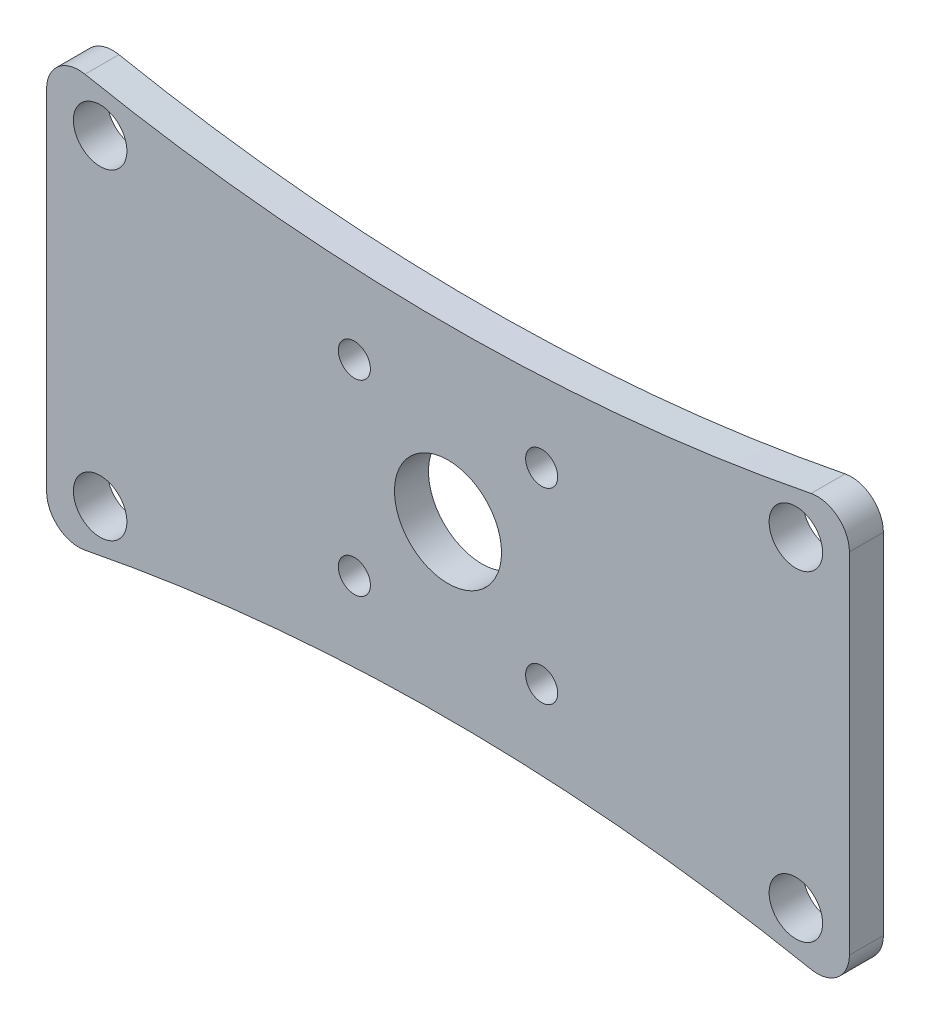
SolidWorks part; units mm, degrees
ref_plane "Front Plane" through (0, 0, 0) normal (0, 0, 1) x (1, 0, 0)
ref_plane "Top Plane" through (0, 0, 0) normal (0, 1, 0) x (1, 0, 0)
ref_plane "Right Plane" through (0, 0, 0) normal (1, 0, 0) x (0, 0, -1)
sketch "Sketch1" plane through (0, 0, 0) normal (0, 0, 1) x (1, 0, 0)
  line L0 (-37.5, 20) -> (37.5, -20) construction
  line L1 (-37.5, 20) -> (37.5, 20)
  line L2 (-37.5, 20) -> (-37.5, -20)
  line L3 (-37.5, -20) -> (37.5, -20)
  line L4 (37.5, 20) -> (37.5, -20)
  line L5 (-32.5, 15) -> (32.5, -15) construction
  line L6 (-32.5, 15) -> (32.5, 15) construction
  line L7 (-32.5, 15) -> (-32.5, -15) construction
  line L8 (-32.5, -15) -> (32.5, -15) construction
  line L9 (32.5, 15) -> (32.5, -15) construction
  line L10 (-8.75, 8.75) -> (8.75, -8.75) construction
  line L11 (-8.75, 8.75) -> (8.75, 8.75) construction
  line L12 (-8.75, 8.75) -> (-8.75, -8.75) construction
  line L13 (-8.75, -8.75) -> (8.75, -8.75) construction
  line L14 (8.75, 8.75) -> (8.75, -8.75) construction
  circle A0 centre (-32.5, 15) radius 2.5
  circle A1 centre (32.5, 15) radius 2.5
  circle A2 centre (32.5, -15) radius 2.5
  circle A3 centre (-32.5, -15) radius 2.5
  circle A4 centre (-8.75, 8.75) radius 1.5
  circle A5 centre (8.75, 8.75) radius 1.5
  circle A6 centre (8.75, -8.75) radius 1.5
  circle A7 centre (-8.75, -8.75) radius 1.5
  point P4 (0, 0)
  point P10 (0, 0)
  point P23 (0, 0)
  dimension "D5" = 5
  dimension "D7" = 3
  dimension "D1" = 40
  dimension "D2" = 75
  dimension "D3" = 30
  dimension "D4" = 65
  dimension "D6" = 17.5
extrude "Boss-Extrude1" add sketch "Sketch1" along normal blind 3.175
sketch "Sketch2" plane through (0, 0, 3.175) normal (0, 0, 1) x (1, 0, 0)
  circle A0 centre (0, 190.9349) radius 175
  circle A1 centre (0, -190.9349) radius 175
  dimension "D1" = 350
extrude "Cut-Extrude1" cut sketch "Sketch2" against normal blind 3.175
fillet "Fillet1" radius 3 4 edges at (37.5, 20, 1.5875) (37.5, -20, 1.5875) (-37.5, -20, 1.5875) (-37.5, 20, 1.5875)
sketch "Sketch3" plane through (0, 0, 3.175) normal (0, 0, 1) x (1, 0, 0)
  circle A0 centre (0, 0) radius 5
  dimension "D1" = 10
extrude "Cut-Extrude2" cut sketch "Sketch3" against normal blind 3.175
